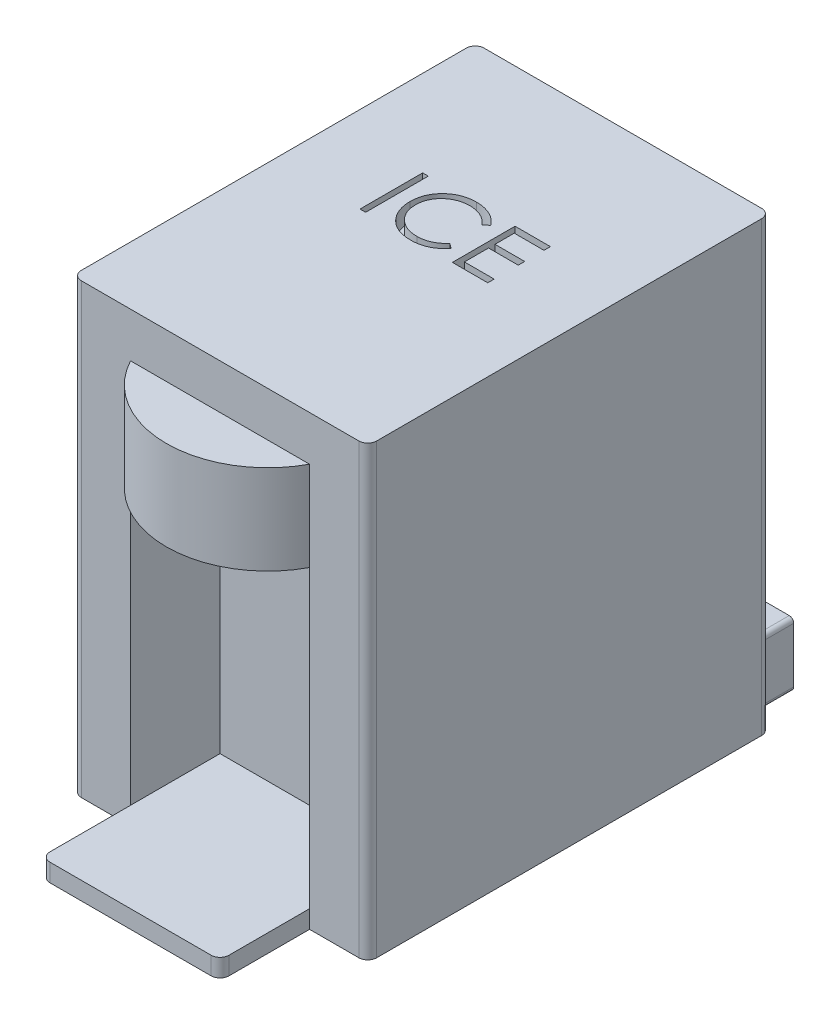
SolidWorks part; units mm, degrees
ref_plane "Front Plane" through (0, 0, 0) normal (0, 0, 1) x (1, 0, 0)
ref_plane "Top Plane" through (0, 0, 0) normal (0, 1, 0) x (1, 0, 0)
ref_plane "Right Plane" through (0, 0, 0) normal (1, 0, 0) x (0, 0, -1)
sketch "Sketch1" plane through (0, 0, 0) normal (0, 1, 0) x (1, 0, 0)
  line L1 (-165, -225) -> (165, -225)
  line L2 (-165, -225) -> (-165, 225)
  line L3 (-165, 225) -> (165, 225)
  line L4 (165, -225) -> (165, 225)
  line L5 (-165, -225) -> (165, 225) construction
  line L6 (-165, 225) -> (165, -225) construction
  point P0 (0, 0)
  dimension "D1" = 330
  dimension "D2" = 450
extrude "Boss-Extrude1" add sketch "Sketch1" along normal blind 500
sketch "Sketch2" plane through (0, 0, 225) normal (0, 0, 1) x (1, 0, 0)
  line L0 (-165, 0) -> (165, 0) construction
  line L1 (-100, 0) -> (100, 0)
  line L2 (-100, 0) -> (-100, 350)
  line L3 (-100, 350) -> (100, 350)
  line L4 (100, 0) -> (100, 350)
  point P6 (0, 0)
  dimension "D1" = 200
  dimension "D2" = 350
extrude "Cut-Extrude1" cut sketch "Sketch2" against normal blind 100
sketch "Sketch3" plane through (0, 350, 0) normal (0, -1, 0) x (1, 0, 0)
  line L0 (100, 225) -> (-100, 225) construction
  line L1 (100, 225) -> (-100, 225)
  arc A0 (-100, 225) -> (100, 225) centre (0, 171.6242) cw
extrude "Boss-Extrude2" add sketch "Sketch3" against normal blind 100
sketch "Sketch4" plane through (0, 0, 125) normal (0, 0, 1) x (1, 0, 0)
  line L0 (100, 0) -> (100, 350) construction
  line L1 (-100, 0) -> (100, 0)
  line L2 (-100, 0) -> (-100, 20)
  line L3 (-100, 20) -> (100, 20)
  line L4 (100, 0) -> (100, 20)
  dimension "D1" = 20
extrude "Boss-Extrude3" add sketch "Sketch4" along normal blind 200
sketch "Sketch5" plane through (0, 350, 0) normal (0, -1, 0) x (1, 0, 0)
  circle A0 centre (0, 203.1713) radius 58.985
extrude "Cut-Extrude2" cut sketch "Sketch5" against normal blind 50
fillet "Fillet1" radius 10 4 edges at (165, 250, 225) (-165, 250, 225) (-165, 250, -225) (165, 250, -225)
sketch "Sketch6" plane through (0, 0, -225) normal (0, 0, -1) x (-1, 0, 0)
  line L0 (-155, 0) -> (155, 0) construction
  line L1 (-140.8441, 0) -> (-32.0502, 0)
  line L2 (-140.8441, 0) -> (-140.8441, 71.4886)
  line L3 (-140.8441, 71.4886) -> (-32.0502, 71.4886)
  line L4 (-32.0502, 0) -> (-32.0502, 71.4886)
extrude "Boss-Extrude4" add sketch "Sketch6" along normal blind 50
fillet "Fillet2" radius 5 4 edges at (140.8441, 0, -250) (140.8441, 71.4886, -250) (32.0502, 0, -250) (32.0502, 71.4886, -250)
fillet "Fillet3" radius 10 2 edges at (-100, 10, 325) (100, 10, 325)
sketch "Sketch7" plane through (0, 500, 0) normal (0, 1, 0) x (1, 0, 0)
  line L0 (-165, 0) -> (165, 0) construction
  line L1 (-165, 215) -> (-165, -215) construction
  line L2 (165, -215) -> (165, 215) construction
  text T0 "ICE" font "Century Gothic" height 70
extrude "Cut-Extrude3" cut sketch "Sketch7" against normal blind 20
